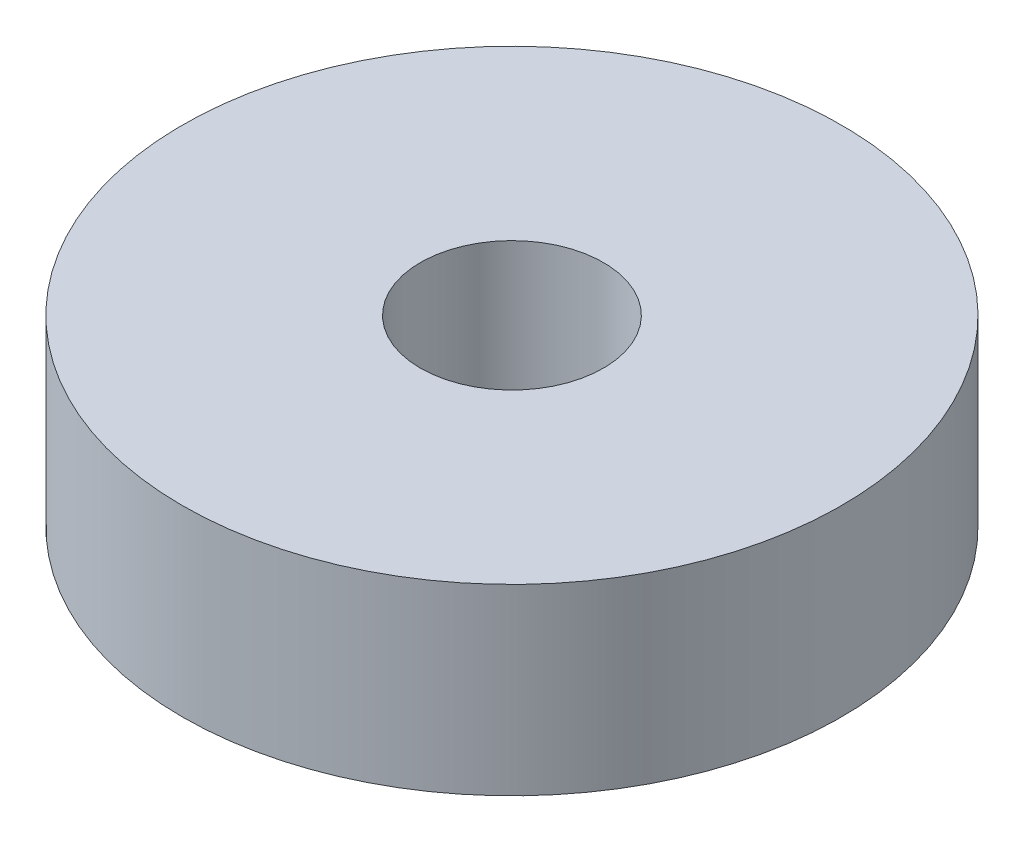
SolidWorks part; units mm, degrees
ref_plane "Front Plane" through (0, 0, 0) normal (0, 0, 1) x (1, 0, 0)
ref_plane "Top Plane" through (0, 0, 0) normal (0, 1, 0) x (1, 0, 0)
ref_plane "Right Plane" through (0, 0, 0) normal (1, 0, 0) x (0, 0, -1)
sketch "Sketch1" plane through (0, 0, 0) normal (0, 1, 0) x (1, 0, 0)
  circle A0 centre (0, 0) radius 9
  circle A1 centre (0, 0) radius 2.5
extrude "Boss-Extrude1" add sketch "Sketch1" along normal blind 5
